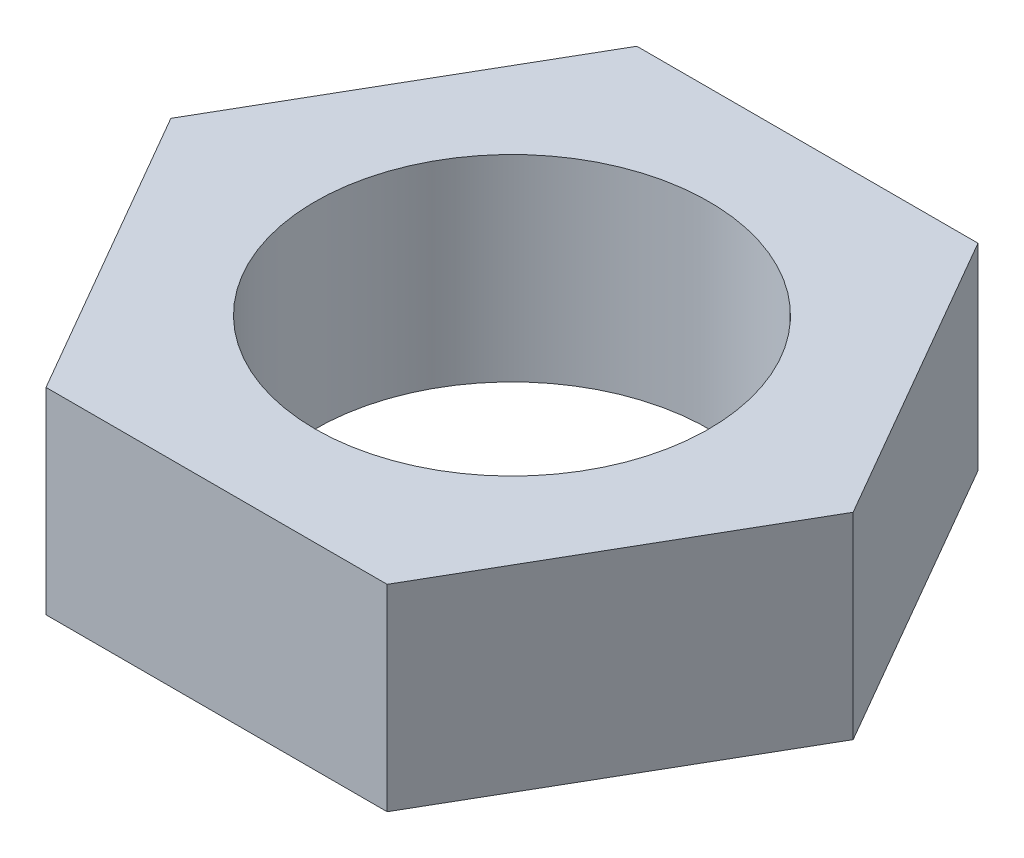
SolidWorks part; units mm, degrees
ref_plane "Front Plane" through (0, 0, 0) normal (0, 0, 1) x (1, 0, 0)
ref_plane "Top Plane" through (0, 0, 0) normal (0, 1, 0) x (1, 0, 0)
ref_plane "Right Plane" through (0, 0, 0) normal (1, 0, 0) x (0, 0, -1)
sketch "Sketch1" plane through (0, 0, 0) normal (0, 1, 0) x (1, 0, 0)
  line L1 (8.6603, 0) -> (4.3301, 7.5)
  line L2 (4.3301, 7.5) -> (-4.3301, 7.5)
  line L3 (-4.3301, 7.5) -> (-8.6603, 0)
  line L4 (-8.6603, 0) -> (-4.3301, -7.5)
  line L5 (-4.3301, -7.5) -> (4.3301, -7.5)
  line L6 (4.3301, -7.5) -> (8.6603, 0)
  circle A0 centre (0, 0) radius 7.5 construction
  circle A1 centre (0, 0) radius 5
  point P10 (0, 0)
  dimension "D2" = 10
  dimension "D1" = 15
extrude "Boss-Extrude1" add sketch "Sketch1" along normal blind 5
